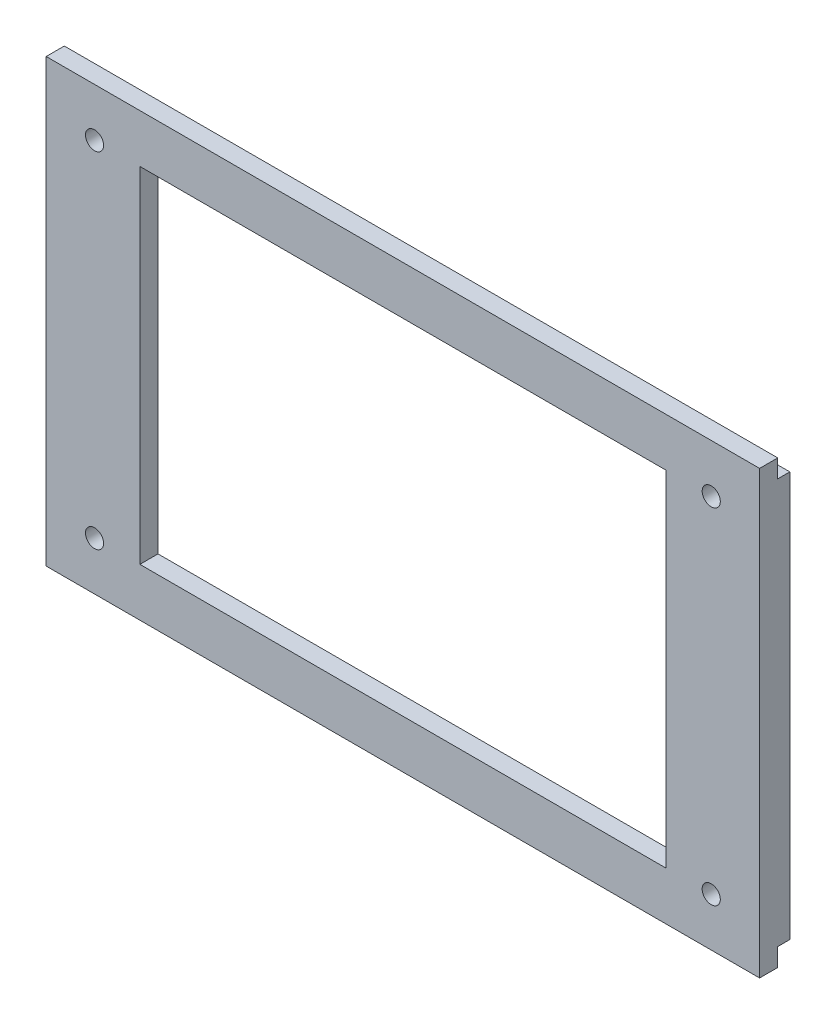
SolidWorks part; units mm, degrees
ref_plane "前视基准面" through (0, 0, 0) normal (0, 0, 1) x (1, 0, 0)
ref_plane "上视基准面" through (0, 0, 0) normal (0, 1, 0) x (1, 0, 0)
ref_plane "右视基准面" through (0, 0, 0) normal (1, 0, 0) x (0, 0, -1)
other "Configuration Table"
sketch "草图1" plane through (0, 0, 0) normal (0, 0, 1) x (1, 0, 0)
  line L0 (-19.8645, 21.6557) -> (98.1355, 21.6557)
  line L1 (98.1355, 21.6557) -> (98.1355, -51.3443)
  line L2 (98.1355, -51.3443) -> (-19.8645, -51.3443)
  line L3 (-19.8645, 21.6557) -> (-19.8645, -51.3443)
  line L4 (-19.8645, 21.6557) -> (-19.8645, 10.6557)
  line L5 (-19.8645, 21.6557) -> (-6.8645, 21.6557)
  line L6 (-19.8645, -51.3443) -> (-14.8645, -51.3443)
  line L7 (-19.8645, 21.6557) -> (-7.3645, 21.6557)
  line L8 (98.1355, 21.6557) -> (98.1355, 10.6557)
  line L9 (-19.8645, 21.6557) -> (-4.3645, 21.6557)
  line L11 (-19.8645, 21.6557) -> (-11.8645, 21.6557)
  line L13 (-19.8645, -51.3443) -> (-11.8645, -51.3443)
  line L15 (98.1355, -51.3443) -> (98.1355, -43.3443)
  line L18 (-4.3645, 13.6557) -> (82.6355, 13.6557)
  line L19 (82.6355, 13.6557) -> (82.6355, -43.3443)
  line L20 (82.6355, -43.3443) -> (-4.3645, -43.3443)
  line L21 (-4.3645, -43.3443) -> (-4.3645, 13.6557)
  circle A4 centre (-11.8645, 13.6557) radius 1.5
  circle A5 centre (90.1355, 13.6557) radius 1.5
  circle A6 centre (90.1355, -43.3443) radius 1.5
  circle A7 centre (-11.8645, -43.3443) radius 1.5
extrude "凸台-拉伸2" add sketch "草图1" along normal blind 3 contours L0 L3 L2 L1 L5 L9 A7 A6 A5 A4 L20 L21 L18 L19
sketch "草图3" plane through (0, 0, 0) normal (0, 0, -1) x (-1, 0, 0)
  line L6 (-98.1355, 18.6557) -> (-98.1355, -48.3443)
  line L7 (-95.1355, 18.6557) -> (-98.1355, 18.6557)
  line L8 (-95.1355, -48.3443) -> (-95.1355, 18.6557)
  line L9 (-98.1355, -48.3443) -> (-95.1355, -48.3443)
extrude "凸台-拉伸3" add sketch "草图3" along normal blind 2
